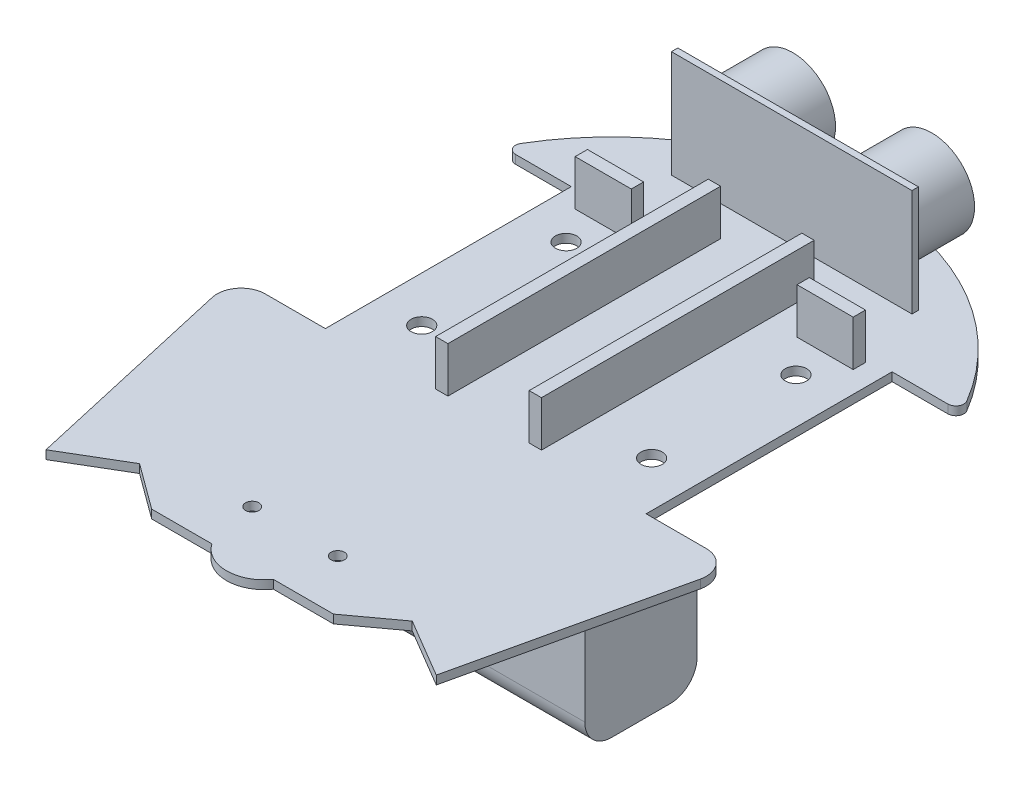
SolidWorks part; units mm, degrees
ref_plane "Front Plane" through (0, 0, 0) normal (0, 0, 1) x (1, 0, 0)
ref_plane "Top Plane" through (0, 0, 0) normal (0, 1, 0) x (1, 0, 0)
ref_plane "Right Plane" through (0, 0, 0) normal (1, 0, 0) x (0, 0, -1)
sketch "Sketch4" plane through (0, 0, 0) normal (0, 1, 0) x (1, 0, 0)
  line L0 (-210.9646, 203.1802) -> (-119.4646, 203.1802) construction
  dimension "D1" = 91.5
sketch "Sketch5" plane through (0, 0, 0) normal (0, 1, 0) x (1, 0, 0)
  line L0 (0, -1065.1986) -> (0, 52194.7329) construction
  line L1 (-25.5, 9.2272) -> (-17, 3)
  line L2 (-17, 3) -> (-5.7446, 3)
  line L3 (-36.5, 2.7272) -> (-25.5, 9.2272)
  line L4 (-45.6383, 42.981) -> (-36.5, 2.7272)
  line L5 (-30, 48.4772) -> (-41.25, 48.4772)
  line L6 (-30, 48.4772) -> (-30, 94.4772)
  line L7 (-40.4239, 94.4772) -> (-30, 94.4772)
  line L8 (40.4239, 94.4772) -> (30, 94.4772)
  line L9 (30, 48.4772) -> (30, 94.4772)
  line L10 (30, 48.4772) -> (41.25, 48.4772)
  line L11 (45.6383, 42.981) -> (36.5, 2.7272)
  line L12 (36.5, 2.7272) -> (25.5, 9.2272)
  line L13 (17, 3) -> (5.7446, 3)
  line L14 (25.5, 9.2272) -> (17, 3)
  arc A0 (-5.7446, 3) -> (5.7446, 3) centre (0, 7) ccw
  arc A1 (-45.6383, 42.981) -> (-41.25, 48.4772) centre (-41.25, 43.9772) cw
  arc A3 (41.714, 96.7424) -> (-41.714, 96.7424) centre (0, 72) ccw
  arc A4 (-41.714, 96.7424) -> (-40.4239, 94.4772) centre (-40.4239, 95.9772) ccw
  arc A5 (41.714, 96.7424) -> (40.4239, 94.4772) centre (40.4239, 95.9772) cw
  arc A6 (45.6383, 42.981) -> (41.25, 48.4772) centre (41.25, 43.9772) ccw
  dimension "D1" = 14
  dimension "D2" = 4.5
  dimension "D3" = 1.5
  dimension "D6" = 91.5
  dimension "D15" = 72
  dimension "D16" = 48.5
  dimension "D4" = 34
  dimension "D5" = 73
  dimension "D7" = 51
  dimension "D8" = 60
  dimension "D9" = 4
  dimension "D10" = 7
  dimension "D11" = 6.2272
  dimension "D12" = 6.5
  dimension "D13" = 45.75
  dimension "D14" = 46
extrude "Boss-Extrude1" add sketch "Sketch5" against normal blind 1.6
sketch "Sketch6" plane through (0, 0, 0) normal (0, 1, 0) x (1, 0, 0)
  line L0 (0, -1000) -> (0, 49000) construction
  line L1 (5.7446, 3) -> (17, 3) construction
  line L2 (-22.5, 105.7) -> (22.5, 105.7)
  line L3 (-22.5, 105.7) -> (-22.5, 106.9)
  line L4 (-22.5, 106.9) -> (22.5, 106.9)
  line L5 (22.5, 105.7) -> (22.5, 106.9)
  dimension "D1" = 45
  dimension "D2" = 1.2
  dimension "D3" = 102.7
extrude "Boss-Extrude2" add sketch "Sketch6" along normal blind 20
sketch "Sketch7" plane through (0, 0, -106.9) normal (0, 0, -1) x (-1, 0, 0)
  line L0 (0, -5.238) -> (0, 22.7865) construction
  line L1 (-22.5, 20) -> (22.5, 20) construction
  circle A0 centre (-13, 10) radius 8
  circle A1 centre (13, 10) radius 8
  dimension "D1" = 16
  dimension "D2" = 26
  dimension "D3" = 10
extrude "Boss-Extrude3" add sketch "Sketch7" along normal blind 12
sketch "Sketch10" plane through (0, -1.6, 0) normal (0, -1, 0) x (1, 0, 0)
  line L0 (0, -1000) -> (0, 49000) construction
  line L2 (-40, -48) -> (40, -48)
  line L3 (-40, -48) -> (-40, -27)
  line L4 (-40, -27) -> (40, -27)
  line L5 (40, -48) -> (40, -27)
  dimension "D1" = 80
  dimension "D2" = 21
  dimension "D3" = 27
extrude "Boss-Extrude4" add sketch "Sketch10" along normal blind 21.4
fillet "Fillet1" radius 5 2 edges at (0, -23, -27) (0, -23, -48)
sketch "Sketch11" plane through (0, 0, 0) normal (0, 1, 0) x (1, 0, 0)
  line L0 (0, -1000) -> (0, 49000) construction
  line L1 (-17, 3) -> (-5.7446, 3) construction
  circle A0 centre (-8, 12.8) radius 1.25
  circle A1 centre (-21.5, 58) radius 2
  circle A2 centre (-21.5, 85) radius 2
  circle A3 centre (-15, 99) radius 1.5
  circle A4 centre (15, 99) radius 1.5
  circle A5 centre (21.5, 85) radius 2
  circle A6 centre (21.5, 58) radius 2
  circle A7 centre (8, 12.8) radius 1.25
  dimension "D1" = 2.5
  dimension "D2" = 3
  dimension "D3" = 4
  dimension "D4" = 16
  dimension "D5" = 12.8
  dimension "D6" = 58
  dimension "D7" = 27
  dimension "D8" = 43
  dimension "D9" = 30
  dimension "D10" = 96
extrude "Cut-Extrude1" cut sketch "Sketch11" against normal up to next
sketch "Sketch12" plane through (0, 0, 0) normal (0, 1, 0) x (1, 0, 0)
  line L0 (0, -1000) -> (0, 49000) construction
  line L1 (-17, 3) -> (-5.7446, 3) construction
  line L2 (-9.9, 100) -> (-7.6, 100)
  line L3 (-9.9, 100) -> (-9.9, 49)
  line L4 (-9.9, 49) -> (-7.6, 49)
  line L5 (-7.6, 100) -> (-7.6, 49)
  line L6 (-26, 93.5) -> (-15.5, 93.5)
  line L7 (-26, 93.5) -> (-26, 91.2)
  line L8 (-26, 91.2) -> (-15.5, 91.2)
  line L9 (-15.5, 93.5) -> (-15.5, 91.2)
  line L11 (15.5, 93.5) -> (15.5, 91.2)
  line L12 (26, 91.2) -> (15.5, 91.2)
  line L13 (26, 93.5) -> (26, 91.2)
  line L14 (26, 93.5) -> (15.5, 93.5)
  line L15 (7.6, 100) -> (7.6, 49)
  line L16 (9.9, 49) -> (7.6, 49)
  line L17 (9.9, 100) -> (9.9, 49)
  line L18 (9.9, 100) -> (7.6, 100)
  line L20 (-17, 3) -> (-5.7446, 3) construction
  dimension "D1" = 51
  dimension "D2" = 46
  dimension "D3" = 2.3
  dimension "D4" = 15.2
  dimension "D5" = 2.3
  dimension "D6" = 88.2
  dimension "D7" = 10.5
  dimension "D8" = 31
extrude "Boss-Extrude5" add sketch "Sketch12" along normal blind 8.5
ref_plane "Plane1" through (0, 0, -71.1772) normal (0, 0, 1) x (1, 0, 0)
sketch "Sketch13" plane through (0, -1.6, 0) normal (0, -1, 0) x (1, 0, 0)
  line L0 (0, -1000) -> (0, 49000) construction
  line L1 (1.5, -106.5) -> (1.5, -116.7)
  line L2 (-6.9, -106.5) -> (-1.5, -106.5)
  line L3 (-21.8, -101.9) -> (-16.4, -101.9)
  line L4 (-21.8, -101.9) -> (-21.8, -112.1)
  line L5 (-21.8, -112.1) -> (-16.4, -112.1)
  line L6 (-16.4, -101.9) -> (-16.4, -112.1)
  line L11 (-6.9, -106.5) -> (-6.9, -116.7)
  line L12 (-6.9, -116.7) -> (-1.5, -116.7)
  line L13 (-1.5, -106.5) -> (-1.5, -116.7)
  line L14 (6.9, -116.7) -> (1.5, -116.7)
  line L15 (6.9, -106.5) -> (6.9, -116.7)
  line L16 (16.4, -101.9) -> (16.4, -112.1)
  line L17 (21.8, -112.1) -> (16.4, -112.1)
  line L18 (21.8, -101.9) -> (21.8, -112.1)
  line L19 (21.8, -101.9) -> (16.4, -101.9)
  line L20 (6.9, -106.5) -> (1.5, -106.5)
  circle A0 centre (-15, -99) radius 1.5 construction
  dimension "D1" = 5.4
  dimension "D2" = 10.2
  dimension "D3" = 32.8
  dimension "D4" = 9.5
  dimension "D5" = 4.6
  dimension "D6" = 14.6
extrude "Boss-Extrude7" add sketch "Sketch13" along normal blind 5
